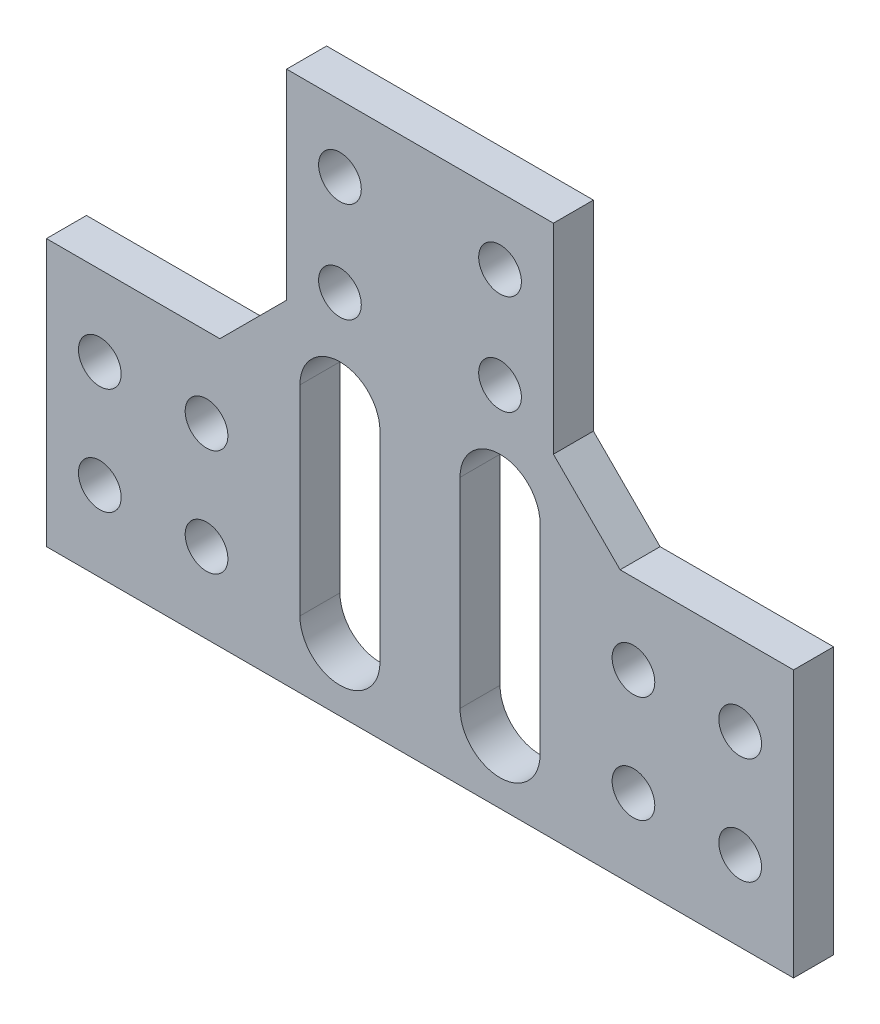
SolidWorks part; units mm, degrees
material "Thornel VCB-20 碳布"
ref_plane "前视基准面" through (0, 0, 0) normal (0, 0, 1) x (1, 0, 0)
ref_plane "上视基准面" through (0, 0, 0) normal (0, 1, 0) x (1, 0, 0)
ref_plane "右视基准面" through (0, 0, 0) normal (1, 0, 0) x (0, 0, -1)
other "Configuration Table"
sketch "草图1" plane through (0, 0, 0) normal (0, 0, 1) x (1, 0, 0)
  line L0 (0, 0) -> (56, 0)
  line L1 (56, 0) -> (56, 20)
  line L2 (56, 20) -> (43, 20)
  line L3 (43, 20) -> (38, 25)
  line L4 (38, 25) -> (38, 40)
  line L5 (38, 40) -> (18, 40)
  line L6 (18, 40) -> (18, 25)
  line L7 (18, 25) -> (13, 20)
  line L8 (13, 20) -> (0, 20)
  line L9 (0, 20) -> (0, 0)
  line L10 (18, 25) -> (38, 25) construction
  dimension "D1" = 20
  dimension "D2" = 20
  dimension "D3" = 45
  dimension "D4" = 45
  dimension "D5" = 18
  dimension "D6" = 20
  dimension "D7" = 15
extrude "凸台-拉伸1" add sketch "草图1" along normal blind 3
sketch "草图2" plane through (0, 0, 3) normal (0, 0, 1) x (1, 0, 0)
  line L0 (38, 25) -> (38, 40) construction
  line L1 (22, 35) -> (34, 35) construction
  line L2 (22, 35) -> (22, 27.5) construction
  line L3 (22, 27.5) -> (34, 27.5) construction
  line L4 (34, 35) -> (34, 27.5) construction
  line L5 (0, 20) -> (0, 0) construction
  line L6 (38, 40) -> (18, 40) construction
  line L7 (4, 14) -> (52, 14) construction
  line L8 (4, 14) -> (4, 6) construction
  line L9 (4, 6) -> (52, 6) construction
  line L10 (52, 14) -> (52, 6) construction
  line L11 (56, 0) -> (56, 20) construction
  line L12 (56, 20) -> (43, 20) construction
  line L13 (0, 0) -> (56, 0) construction
  line L17 (22, 27.5) -> (34, 27.5) construction
  line L18 (22, 27.5) -> (22, 20) construction
  line L19 (22, 20) -> (34, 20) construction
  line L20 (34, 27.5) -> (34, 20) construction
  circle A0 centre (22, 35) radius 1.6
  circle A1 centre (34, 35) radius 1.6
  circle A2 centre (22, 27.5) radius 1.6
  circle A3 centre (34, 27.5) radius 1.6
  circle A4 centre (4, 14) radius 1.6
  circle A5 centre (4, 6) radius 1.6
  circle A6 centre (12, 14) radius 1.6
  circle A7 centre (12, 6) radius 1.6
  circle A8 centre (52, 14) radius 1.6
  circle A9 centre (52, 6) radius 1.6
  circle A10 centre (44, 6) radius 1.6
  circle A11 centre (44, 14) radius 1.6
  circle A14 centre (22, 20) radius 1.6 construction
  circle A15 centre (34, 20) radius 1.6 construction
  circle A16 centre (20, 14) radius 1.6 construction
  circle A17 centre (20, 6) radius 1.6 construction
  circle A18 centre (36, 14) radius 1.6 construction
  circle A19 centre (36, 6) radius 1.6 construction
  dimension "D5" = 3.2
  dimension "D10" = 3.2
  dimension "D16" = 8
  dimension "D1" = 12
  dimension "D2" = 4
  dimension "D3" = 5
  dimension "D4" = 7.5
  dimension "D6" = 4
  dimension "D7" = 4
  dimension "D8" = 6
  dimension "D9" = 6
  dimension "D11" = 8
  dimension "D12" = 8
  dimension "D13" = 8
  dimension "D14" = 8
  dimension "D15" = 8
  dimension "D17" = 8
  dimension "D18" = 8
  dimension "D19" = 7.5
extrude "切除-拉伸1" cut sketch "草图2" against normal blind 3
sketch "草图3" plane through (0, 0, 3) normal (0, 0, 1) x (1, 0, 0)
  line L0 (22, 20) -> (22, 5) construction
  line L1 (25, 20) -> (25, 5)
  line L2 (19, 20) -> (19, 5)
  line L3 (34, 20) -> (34, 5) construction
  line L4 (37, 20) -> (37, 5)
  line L5 (31, 20) -> (31, 5)
  line L6 (0, 0) -> (56, 0) construction
  arc A0 (25, 20) -> (19, 20) centre (22, 20) ccw
  arc A1 (19, 5) -> (25, 5) centre (22, 5) ccw
  arc A2 (37, 20) -> (31, 20) centre (34, 20) ccw
  arc A3 (31, 5) -> (37, 5) centre (34, 5) ccw
  point P2 (22, 12.5)
  point P7 (34, 12.5)
  point P18 (21, 13.4246)
  point P19 (21, 15.5708)
  dimension "D5" = 3
  dimension "D1" = 9
  dimension "D2" = 9
  dimension "D3" = 12.5
  dimension "D4" = 12.5
  dimension "D6" = 15
extrude "切除-拉伸2" cut sketch "草图3" against normal blind 10
